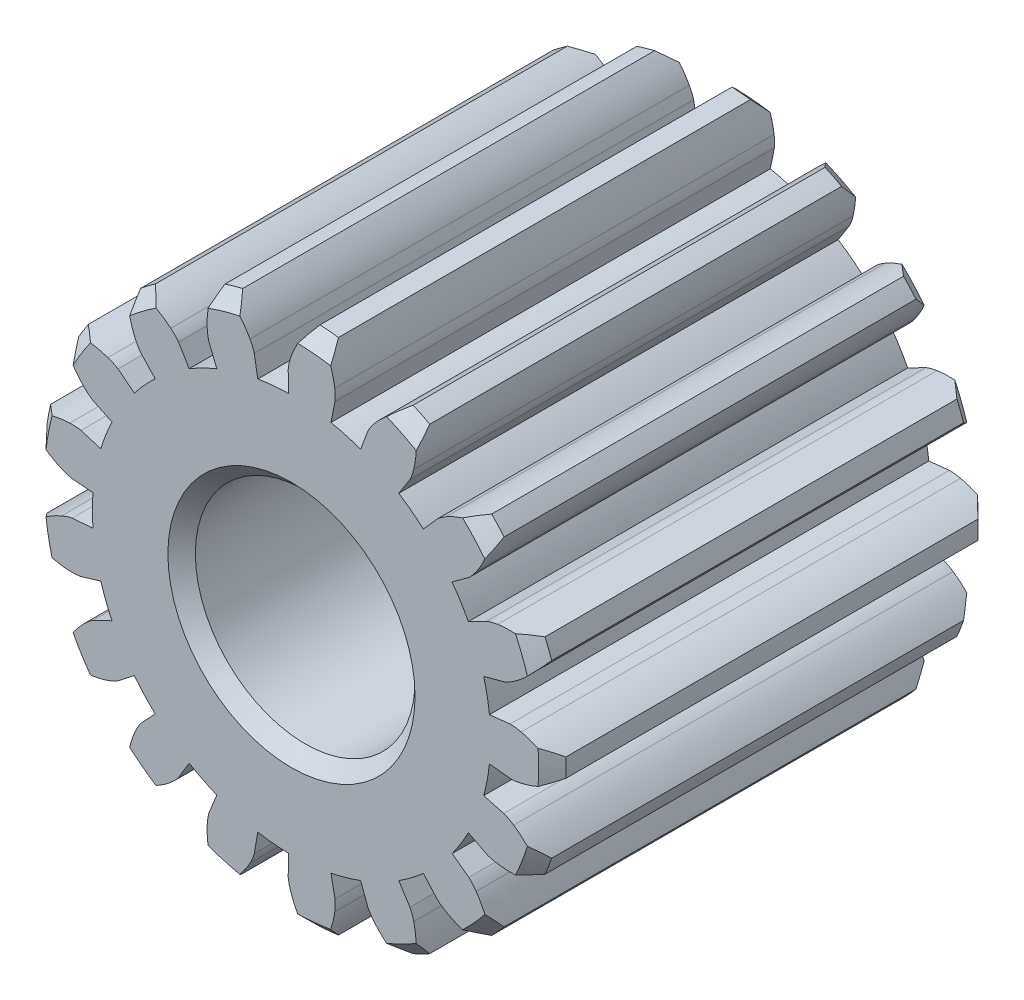
SolidWorks part; units mm, degrees
ref_plane "Front Plane" through (0, 0, 0) normal (0, 0, 1) x (1, 0, 0)
ref_plane "Top Plane" through (0, 0, 0) normal (0, 1, 0) x (1, 0, 0)
ref_plane "Right Plane" through (0, 0, 0) normal (1, 0, 0) x (0, 0, -1)
sketch "Model" plane through (0, 0, 0) normal (0, 0, 1) x (1, 0, 0)
  line L0 (3.6042, -0.3879) -> (3.9793, -0.4283)
  line L1 (3.9793, 0.4283) -> (3.6042, 0.3879)
  line L2 (3.5009, 0.9403) -> (3.8653, 1.0381)
  line L3 (3.5559, 1.8368) -> (3.2207, 1.6637)
  line L4 (2.9249, 2.1415) -> (3.2293, 2.3643)
  line L5 (2.6522, 2.9973) -> (2.4022, 2.7148)
  line L6 (1.9538, 3.0534) -> (2.1571, 3.3712)
  line L7 (1.3903, 3.753) -> (1.2593, 3.3992)
  line L8 (0.7188, 3.553) -> (0.7936, 3.9228)
  line L9 (-0.0593, 4.0018) -> (-0.0537, 3.6246)
  line L10 (-0.6132, 3.5728) -> (-0.6771, 3.9446)
  line L11 (-1.5009, 3.7102) -> (-1.3594, 3.3604)
  line L12 (-1.8624, 3.11) -> (-2.0563, 3.4336)
  line L13 (-2.7398, 2.9174) -> (-2.4816, 2.6424)
  line L14 (-2.8601, 2.2272) -> (-3.1578, 2.4589)
  line L15 (-3.6087, 1.7307) -> (-3.2685, 1.5676)
  line L16 (-3.4715, 1.0436) -> (-3.8328, 1.1522)
  line L17 (-3.9902, 0.3102) -> (-3.6141, 0.281)
  line L18 (-3.6141, -0.281) -> (-3.9902, -0.3102)
  line L19 (-3.8328, -1.1522) -> (-3.4715, -1.0436)
  line L20 (-3.2685, -1.5676) -> (-3.6087, -1.7307)
  line L21 (-3.1578, -2.4589) -> (-2.8601, -2.2272)
  line L22 (-2.4816, -2.6424) -> (-2.7398, -2.9174)
  line L23 (-2.0563, -3.4336) -> (-1.8624, -3.11)
  line L24 (-1.3594, -3.3604) -> (-1.5009, -3.7102)
  line L25 (-0.6771, -3.9446) -> (-0.6132, -3.5728)
  line L26 (-0.0537, -3.6246) -> (-0.0593, -4.0018)
  line L27 (0.7936, -3.9228) -> (0.7188, -3.553)
  line L28 (1.2593, -3.3992) -> (1.3903, -3.753)
  line L29 (2.1571, -3.3712) -> (1.9538, -3.0534)
  line L30 (2.4022, -2.7148) -> (2.6522, -2.9973)
  line L31 (3.2293, -2.3643) -> (2.9249, -2.1415)
  line L32 (3.2207, -1.6637) -> (3.5559, -1.8368)
  line L33 (3.8653, -1.0381) -> (3.5009, -0.9403)
  arc A0 (4.7476, -0.1683) -> (4.7476, 0.1683) centre (0, 0) ccw
  arc A1 (3.6042, 0.3879) -> (3.5009, 0.9403) centre (0, 0) ccw
  arc A2 (4.4878, 1.5581) -> (4.3662, 1.8719) centre (0, 0) ccw
  arc A3 (3.2207, 1.6637) -> (2.9249, 2.1415) centre (0, 0) ccw
  arc A4 (3.6219, 3.0741) -> (3.3951, 3.3228) centre (0, 0) ccw
  arc A5 (2.4022, 2.7148) -> (1.9538, 3.0534) centre (0, 0) ccw
  arc A6 (2.2668, 4.1749) -> (1.9655, 4.3249) centre (0, 0) ccw
  arc A7 (1.2593, 3.3992) -> (0.7188, 3.553) centre (0, 0) ccw
  arc A8 (0.6056, 4.7118) -> (0.2705, 4.7429) centre (0, 0) ccw
  arc A9 (-0.0537, 3.6246) -> (-0.6132, 3.5728) centre (0, 0) ccw
  arc A10 (-1.1374, 4.6124) -> (-1.4611, 4.5203) centre (0, 0) ccw
  arc A11 (-1.3594, 3.3604) -> (-1.8624, 3.11) centre (0, 0) ccw
  arc A12 (-2.7268, 3.8901) -> (-2.9954, 3.6873) centre (0, 0) ccw
  arc A13 (-2.4816, 2.6424) -> (-2.8601, 2.2272) centre (0, 0) ccw
  arc A14 (-3.9479, 2.6424) -> (-4.1251, 2.3562) centre (0, 0) ccw
  arc A15 (-3.2685, 1.5676) -> (-3.4715, 1.0436) centre (0, 0) ccw
  arc A16 (-4.6358, 1.0378) -> (-4.6977, 0.707) centre (0, 0) ccw
  arc A17 (-3.6141, 0.281) -> (-3.6141, -0.281) centre (0, 0) ccw
  arc A18 (-4.6977, -0.707) -> (-4.6358, -1.0378) centre (0, 0) ccw
  arc A19 (-3.4715, -1.0436) -> (-3.2685, -1.5676) centre (0, 0) ccw
  arc A20 (-4.1251, -2.3562) -> (-3.9479, -2.6424) centre (0, 0) ccw
  arc A21 (-2.8601, -2.2272) -> (-2.4816, -2.6424) centre (0, 0) ccw
  arc A22 (-2.9954, -3.6873) -> (-2.7268, -3.8901) centre (0, 0) ccw
  arc A23 (-1.8624, -3.11) -> (-1.3594, -3.3604) centre (0, 0) ccw
  arc A24 (-1.4611, -4.5203) -> (-1.1374, -4.6124) centre (0, 0) ccw
  arc A25 (-0.6132, -3.5728) -> (-0.0537, -3.6246) centre (0, 0) ccw
  arc A26 (0.2705, -4.7429) -> (0.6056, -4.7118) centre (0, 0) ccw
  arc A27 (0.7188, -3.553) -> (1.2593, -3.3992) centre (0, 0) ccw
  arc A28 (1.9655, -4.3249) -> (2.2668, -4.1749) centre (0, 0) ccw
  arc A29 (1.9538, -3.0534) -> (2.4022, -2.7148) centre (0, 0) ccw
  arc A30 (3.3951, -3.3228) -> (3.6219, -3.0741) centre (0, 0) ccw
  arc A31 (2.9249, -2.1415) -> (3.2207, -1.6637) centre (0, 0) ccw
  arc A32 (4.3662, -1.8719) -> (4.4878, -1.5581) centre (0, 0) ccw
  arc A33 (3.5009, -0.9403) -> (3.6042, -0.3879) centre (0, 0) ccw
  circle A34 centre (0, 0) radius 2
  spline S0 degree 3 poles (3.9793, -0.4283) (4.0017, -0.4292) (4.0693, -0.4292) (4.1823, -0.4043) knots 0 0 0 0 1 1 1 1
  spline S1 degree 3 poles (4.1823, -0.4043) (4.3172, -0.374) (4.5108, -0.3086) (4.7476, -0.1683) knots 0 0 0 0 1 1 1 1
  spline S2 degree 3 poles (4.7476, 0.1683) (4.5108, 0.3086) (4.3172, 0.374) (4.1823, 0.4043) knots 0 0 0 0 1 1 1 1
  spline S3 degree 3 poles (4.1823, 0.4043) (4.0693, 0.4292) (4.0017, 0.4292) (3.9793, 0.4283) knots 0 0 0 0 1 1 1 1
  spline S4 degree 3 poles (3.8653, 1.0381) (3.8866, 1.0454) (3.9496, 1.0698) (4.0459, 1.1338) knots 0 0 0 0 1 1 1 1
  spline S5 degree 3 poles (4.0459, 1.1338) (4.1608, 1.2108) (4.3177, 1.3418) (4.4878, 1.5581) knots 0 0 0 0 1 1 1 1
  spline S6 degree 3 poles (4.3662, 1.8719) (4.0948, 1.9172) (3.8906, 1.9083) (3.7538, 1.8878) knots 0 0 0 0 1 1 1 1
  spline S7 degree 3 poles (3.7538, 1.8878) (3.6395, 1.8702) (3.5765, 1.8458) (3.5559, 1.8368) knots 0 0 0 0 1 1 1 1
  spline S8 degree 3 poles (3.2293, 2.3643) (3.2465, 2.3788) (3.2964, 2.4243) (3.3631, 2.5188) knots 0 0 0 0 1 1 1 1
  spline S9 degree 3 poles (3.3631, 2.5188) (3.4424, 2.6321) (3.5414, 2.8109) (3.6219, 3.0741) knots 0 0 0 0 1 1 1 1
  spline S10 degree 3 poles (3.3951, 3.3228) (3.1257, 3.267) (2.9385, 3.1849) (2.8184, 3.1163) knots 0 0 0 0 1 1 1 1
  spline S11 degree 3 poles (2.8184, 3.1163) (2.7181, 3.0587) (2.6682, 3.0132) (2.6522, 2.9973) knots 0 0 0 0 1 1 1 1
  spline S12 degree 3 poles (2.1571, 3.3712) (2.168, 3.3909) (2.198, 3.4514) (2.2261, 3.5636) knots 0 0 0 0 1 1 1 1
  spline S13 degree 3 poles (2.2261, 3.5636) (2.2591, 3.6979) (2.2869, 3.9004) (2.2668, 4.1749) knots 0 0 0 0 1 1 1 1
  spline S14 degree 3 poles (1.9655, 4.3249) (1.7344, 4.1755) (1.5895, 4.0313) (1.5023, 3.924) knots 0 0 0 0 1 1 1 1
  spline S15 degree 3 poles (1.5023, 3.924) (1.4297, 3.834) (1.3995, 3.7735) (1.3903, 3.753) knots 0 0 0 0 1 1 1 1
  spline S16 degree 3 poles (0.7936, 3.9228) (0.7966, 3.9451) (0.8028, 4.0124) (0.7884, 4.1271) knots 0 0 0 0 1 1 1 1
  spline S17 degree 3 poles (0.7884, 4.1271) (0.7708, 4.2643) (0.7234, 4.4631) (0.6056, 4.7118) knots 0 0 0 0 1 1 1 1
  spline S18 degree 3 poles (0.2705, 4.7429) (0.109, 4.5201) (0.0259, 4.3333) (-0.0167, 4.2017) knots 0 0 0 0 1 1 1 1
  spline S19 degree 3 poles (-0.0167, 4.2017) (-0.0519, 4.0916) (-0.0582, 4.0243) (-0.0593, 4.0018) knots 0 0 0 0 1 1 1 1
  spline S20 degree 3 poles (-0.6771, 3.9446) (-0.6823, 3.9664) (-0.7008, 4.0314) (-0.7557, 4.1333) knots 0 0 0 0 1 1 1 1
  spline S21 degree 3 poles (-0.7557, 4.1333) (-0.8217, 4.2548) (-0.9377, 4.4231) (-1.1374, 4.6124) knots 0 0 0 0 1 1 1 1
  spline S22 degree 3 poles (-1.4611, 4.5203) (-1.5312, 4.2542) (-1.5412, 4.0501) (-1.5334, 3.912) knots 0 0 0 0 1 1 1 1
  spline S23 degree 3 poles (-1.5334, 3.912) (-1.5264, 3.7965) (-1.508, 3.7315) (-1.5009, 3.7102) knots 0 0 0 0 1 1 1 1
  spline S24 degree 3 poles (-2.0563, 3.4336) (-2.0691, 3.4521) (-2.1098, 3.506) (-2.1978, 3.5812) knots 0 0 0 0 1 1 1 1
  spline S25 degree 3 poles (-2.1978, 3.5812) (-2.3032, 3.6706) (-2.4722, 3.7857) (-2.7268, 3.8901) knots 0 0 0 0 1 1 1 1
  spline S26 degree 3 poles (-2.9954, 3.6873) (-2.9646, 3.4138) (-2.9002, 3.2198) (-2.843, 3.0939) knots 0 0 0 0 1 1 1 1
  spline S27 degree 3 poles (-2.843, 3.0939) (-2.7948, 2.9888) (-2.7541, 2.9348) (-2.7398, 2.9174) knots 0 0 0 0 1 1 1 1
  spline S28 degree 3 poles (-3.1578, 2.4589) (-3.1764, 2.4716) (-3.2339, 2.5071) (-3.343, 2.5454) knots 0 0 0 0 1 1 1 1
  spline S29 degree 3 poles (-3.343, 2.5454) (-3.4737, 2.5907) (-3.6728, 2.637) (-3.9479, 2.6424) knots 0 0 0 0 1 1 1 1
  spline S30 degree 3 poles (-4.1251, 2.3562) (-3.9976, 2.1123) (-3.8675, 1.9547) (-3.7687, 1.858) knots 0 0 0 0 1 1 1 1
  spline S31 degree 3 poles (-3.7687, 1.858) (-3.6857, 1.7773) (-3.6283, 1.7417) (-3.6087, 1.7307) knots 0 0 0 0 1 1 1 1
  spline S32 degree 3 poles (-3.8328, 1.1522) (-3.8547, 1.1572) (-3.9212, 1.1696) (-4.0368, 1.1659) knots 0 0 0 0 1 1 1 1
  spline S33 degree 3 poles (-4.0368, 1.1659) (-4.175, 1.1609) (-4.3773, 1.1322) (-4.6358, 1.0378) knots 0 0 0 0 1 1 1 1
  spline S34 degree 3 poles (-4.6977, 0.707) (-4.4907, 0.5256) (-4.3124, 0.4256) (-4.1854, 0.3711) knots 0 0 0 0 1 1 1 1
  spline S35 degree 3 poles (-4.1854, 0.3711) (-4.0789, 0.3259) (-4.0125, 0.3134) (-3.9902, 0.3102) knots 0 0 0 0 1 1 1 1
  spline S36 degree 3 poles (-3.9902, -0.3102) (-4.0125, -0.3134) (-4.0789, -0.3259) (-4.1854, -0.3711) knots 0 0 0 0 1 1 1 1
  spline S37 degree 3 poles (-4.1854, -0.3711) (-4.3124, -0.4256) (-4.4907, -0.5256) (-4.6977, -0.707) knots 0 0 0 0 1 1 1 1
  spline S38 degree 3 poles (-4.6358, -1.0378) (-4.3773, -1.1322) (-4.175, -1.1609) (-4.0368, -1.1659) knots 0 0 0 0 1 1 1 1
  spline S39 degree 3 poles (-4.0368, -1.1659) (-3.9212, -1.1696) (-3.8547, -1.1572) (-3.8328, -1.1522) knots 0 0 0 0 1 1 1 1
  spline S40 degree 3 poles (-3.6087, -1.7307) (-3.6283, -1.7417) (-3.6857, -1.7773) (-3.7687, -1.858) knots 0 0 0 0 1 1 1 1
  spline S41 degree 3 poles (-3.7687, -1.858) (-3.8675, -1.9547) (-3.9976, -2.1123) (-4.1251, -2.3562) knots 0 0 0 0 1 1 1 1
  spline S42 degree 3 poles (-3.9479, -2.6424) (-3.6728, -2.637) (-3.4737, -2.5907) (-3.343, -2.5454) knots 0 0 0 0 1 1 1 1
  spline S43 degree 3 poles (-3.343, -2.5454) (-3.2339, -2.5071) (-3.1764, -2.4716) (-3.1578, -2.4589) knots 0 0 0 0 1 1 1 1
  spline S44 degree 3 poles (-2.7398, -2.9174) (-2.7541, -2.9348) (-2.7948, -2.9888) (-2.843, -3.0939) knots 0 0 0 0 1 1 1 1
  spline S45 degree 3 poles (-2.843, -3.0939) (-2.9002, -3.2198) (-2.9646, -3.4138) (-2.9954, -3.6873) knots 0 0 0 0 1 1 1 1
  spline S46 degree 3 poles (-2.7268, -3.8901) (-2.4722, -3.7857) (-2.3032, -3.6706) (-2.1978, -3.5812) knots 0 0 0 0 1 1 1 1
  spline S47 degree 3 poles (-2.1978, -3.5812) (-2.1098, -3.506) (-2.0691, -3.4521) (-2.0563, -3.4336) knots 0 0 0 0 1 1 1 1
  spline S48 degree 3 poles (-1.5009, -3.7102) (-1.508, -3.7315) (-1.5264, -3.7965) (-1.5334, -3.912) knots 0 0 0 0 1 1 1 1
  spline S49 degree 3 poles (-1.5334, -3.912) (-1.5412, -4.0501) (-1.5312, -4.2542) (-1.4611, -4.5203) knots 0 0 0 0 1 1 1 1
  spline S50 degree 3 poles (-1.1374, -4.6124) (-0.9377, -4.4231) (-0.8217, -4.2548) (-0.7557, -4.1333) knots 0 0 0 0 1 1 1 1
  spline S51 degree 3 poles (-0.7557, -4.1333) (-0.7008, -4.0314) (-0.6823, -3.9664) (-0.6771, -3.9446) knots 0 0 0 0 1 1 1 1
  spline S52 degree 3 poles (-0.0593, -4.0018) (-0.0582, -4.0243) (-0.0519, -4.0916) (-0.0167, -4.2017) knots 0 0 0 0 1 1 1 1
  spline S53 degree 3 poles (-0.0167, -4.2017) (0.0259, -4.3333) (0.109, -4.5201) (0.2705, -4.7429) knots 0 0 0 0 1 1 1 1
  spline S54 degree 3 poles (0.6056, -4.7118) (0.7234, -4.4631) (0.7708, -4.2643) (0.7884, -4.1271) knots 0 0 0 0 1 1 1 1
  spline S55 degree 3 poles (0.7884, -4.1271) (0.8028, -4.0124) (0.7966, -3.9451) (0.7936, -3.9228) knots 0 0 0 0 1 1 1 1
  spline S56 degree 3 poles (1.3903, -3.753) (1.3995, -3.7735) (1.4297, -3.834) (1.5023, -3.924) knots 0 0 0 0 1 1 1 1
  spline S57 degree 3 poles (1.5023, -3.924) (1.5895, -4.0313) (1.7344, -4.1755) (1.9655, -4.3249) knots 0 0 0 0 1 1 1 1
  spline S58 degree 3 poles (2.2668, -4.1749) (2.2869, -3.9004) (2.2591, -3.6979) (2.2261, -3.5636) knots 0 0 0 0 1 1 1 1
  spline S59 degree 3 poles (2.2261, -3.5636) (2.198, -3.4514) (2.168, -3.3909) (2.1571, -3.3712) knots 0 0 0 0 1 1 1 1
  spline S60 degree 3 poles (2.6522, -2.9973) (2.6682, -3.0132) (2.7181, -3.0587) (2.8184, -3.1163) knots 0 0 0 0 1 1 1 1
  spline S61 degree 3 poles (2.8184, -3.1163) (2.9385, -3.1849) (3.1257, -3.267) (3.3951, -3.3228) knots 0 0 0 0 1 1 1 1
  spline S62 degree 3 poles (3.6219, -3.0741) (3.5414, -2.8109) (3.4424, -2.6321) (3.3631, -2.5188) knots 0 0 0 0 1 1 1 1
  spline S63 degree 3 poles (3.3631, -2.5188) (3.2964, -2.4243) (3.2465, -2.3788) (3.2293, -2.3643) knots 0 0 0 0 1 1 1 1
  spline S64 degree 3 poles (3.5559, -1.8368) (3.5765, -1.8458) (3.6395, -1.8702) (3.7538, -1.8878) knots 0 0 0 0 1 1 1 1
  spline S65 degree 3 poles (3.7538, -1.8878) (3.8906, -1.9083) (4.0948, -1.9172) (4.3662, -1.8719) knots 0 0 0 0 1 1 1 1
  spline S66 degree 3 poles (4.4878, -1.5581) (4.3177, -1.3418) (4.1608, -1.2108) (4.0459, -1.1338) knots 0 0 0 0 1 1 1 1
  spline S67 degree 3 poles (4.0459, -1.1338) (3.9496, -1.0698) (3.8866, -1.0454) (3.8653, -1.0381) knots 0 0 0 0 1 1 1 1
extrude "Boss-Extrude1" add sketch "Model" along normal blind 8
chamfer "Chamfer1" distance 0.25 angle 45 18 edges at (2, 0, 8) (4.4298, 1.7161, 8) (4.7506, 0, 8) (4.4298, -1.7161, 8) (3.5107, -3.2004, 8) (2.1175, -4.2525, 8) (0.4383, -4.7303, 8) (-1.3001, -4.5692, 8) (-2.8629, -3.791, 8) (-4.039, -2.5009, 8) (-4.6697, -0.8729, 8) (-4.6697, 0.8729, 8) (-4.039, 2.5009, 8) (-2.8629, 3.791, 8) (3.5107, 3.2004, 8) (2.1175, 4.2525, 8) (0.4383, 4.7303, 8) (-1.3001, 4.5692, 8)
chamfer "Chamfer2" distance 0.25 angle 45 18 edges at (2, 0, 0) (-1.3001, 4.5692, 0) (0.4383, 4.7303, 0) (2.1175, 4.2525, 0) (3.5107, 3.2004, 0) (4.4298, 1.7161, 0) (4.7506, 0, 0) (4.4298, -1.7161, 0) (3.5107, -3.2004, 0) (2.1175, -4.2525, 0) (0.4383, -4.7303, 0) (-1.3001, -4.5692, 0) (-2.8629, -3.791, 0) (-4.039, -2.5009, 0) (-4.6697, -0.8729, 0) (-4.6697, 0.8729, 0) (-4.039, 2.5009, 0) (-2.8629, 3.791, 0)
